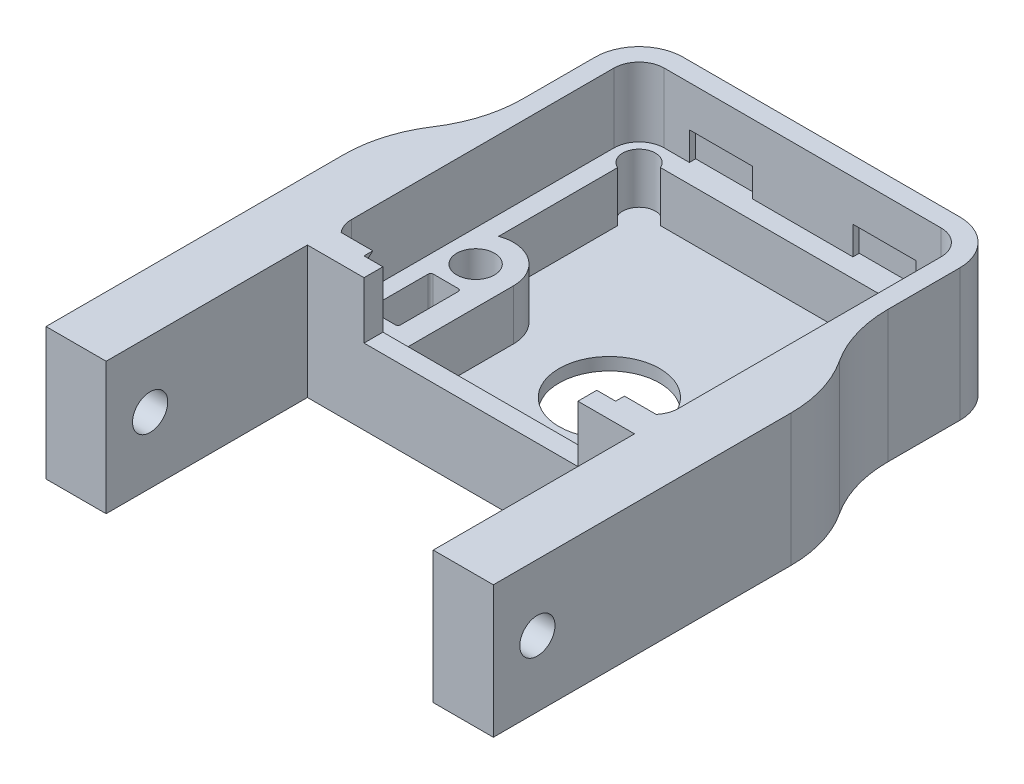
SolidWorks part; units mm, degrees
ref_plane "Front" through (0, 0, 0) normal (0, 0, 1) x (1, 0, 0)
ref_plane "Top" through (0, 0, 0) normal (0, 1, 0) x (1, 0, 0)
ref_plane "Right" through (0, 0, 0) normal (1, 0, 0) x (0, 0, -1)
sketch "Sketch1" plane through (0, 0, 0) normal (0, 1, 0) x (1, 0, 0)
  line L0 (-1.5, 2) -> (-1.5, 22.862)
  line L1 (2, 0) -> (24, 0)
  line L2 (0, 2) -> (0, 22.862)
  line L3 (2, 24.862) -> (24, 24.862)
  line L4 (26, 2) -> (26, 22.862)
  line L5 (2, 26.362) -> (24, 26.362)
  line L6 (27.5, 2) -> (27.5, 22.862)
  line L7 (2, -1.5) -> (24, -1.5)
  line L8 (27.5, 2) -> (27.5, -1.5)
  line L9 (27.5, -1.5) -> (24, -1.5)
  line L10 (-1.5, 2) -> (-1.5, -1.5)
  line L11 (-1.5, -1.5) -> (2, -1.5)
  arc A0 (0, 2) -> (2, 0) centre (2, 2) ccw
  arc A1 (26, 2) -> (24, 0) centre (24, 2) cw
  arc A2 (26, 22.862) -> (24, 24.862) centre (24, 22.862) ccw
  arc A3 (0, 22.862) -> (2, 24.862) centre (2, 22.862) cw
  arc A4 (-1.5, 22.862) -> (2, 26.362) centre (2, 22.862) cw
  arc A5 (27.5, 22.862) -> (24, 26.362) centre (24, 22.862) ccw
  arc A8 (27.5, 2) -> (24, -1.5) centre (24, 2) cw construction
  arc A9 (-1.5, 2) -> (2, -1.5) centre (2, 2) ccw construction
  point P7 (0, 0)
  dimension "D1" = 2
  dimension "D2" = 26
  dimension "D3" = 24.862
  dimension "D4" = 1.5
extrude "Boss-Extrude1" add sketch "Sketch1" along normal blind 9.5
sketch "Sketch3" plane through (0, 0, 0) normal (0, -1, 0) x (1, 0, 0)
  line L0 (24, -26.362) -> (2, -26.362) construction
  line L1 (27.5, 1.5) -> (27.5, -22.862) construction
  line L2 (-1.5, 1.5) -> (27.5, 1.5) construction
  line L3 (-1.5, -22.862) -> (-1.5, 1.5) construction
  line L4 (24, -26.362) -> (2, -26.362)
  line L5 (27.5, 1.5) -> (27.5, -22.862)
  line L6 (-1.5, 1.5) -> (27.5, 1.5)
  line L7 (-1.5, -22.862) -> (-1.5, 1.5)
  arc A0 (-1.5, -22.862) -> (2, -26.362) centre (2, -22.862) ccw construction
  arc A1 (24, -26.362) -> (27.5, -22.862) centre (24, -22.862) ccw construction
  arc A4 (-1.5, -22.862) -> (2, -26.362) centre (2, -22.862) ccw
  arc A5 (24, -26.362) -> (27.5, -22.862) centre (24, -22.862) ccw
extrude "Boss-Extrude2" add sketch "Sketch3" along normal blind 1
sketch "Sketch4" plane through (0, 0, 0) normal (0, 1, 0) x (1, 0, 0)
  line L0 (2, 0) -> (24, 0) construction
  circle A0 centre (13, 9.5) radius 4
  point P8 (13, 0)
  dimension "D1" = 9.5
  dimension "D2" = 8
extrude "Cut-Extrude1" cut sketch "Sketch4" against normal through all both and the other way through all
sketch "Sketch5" plane through (0, 0, 0) normal (0, 1, 0) x (1, 0, 0)
  line L0 (22.8661, 23.362) -> (3.1339, 23.362)
  line L1 (1.5, 21.7281) -> (1.5, 12.1997)
  line L4 (0, 22.862) -> (0, 2)
  line L5 (2, 0) -> (24, 0)
  line L6 (26, 2) -> (26, 22.862)
  line L7 (24, 24.862) -> (2, 24.862)
  line L8 (0, 22.862) -> (0, 2)
  line L9 (2, 0) -> (5.5, 0)
  line L12 (2, 1.5) -> (24, 1.5) construction
  line L13 (5.5, 9.3713) -> (5.5, 0)
  line L14 (13, 63.668) -> (13, -12.944) construction
  line L15 (1.5, 2) -> (3.5, 2)
  line L16 (1.5, 22.862) -> (1.5, 2) construction
  line L17 (24, 23.362) -> (2, 23.362) construction
  line L18 (1.3, 2.2) -> (1.3, 6.8)
  line L19 (1.5, 7) -> (3.5, 7)
  line L20 (3.7, 2.2) -> (3.7, 6.8)
  line L21 (22.3, 2.2) -> (22.3, 6.8)
  line L22 (24, 24.862) -> (2, 24.862) construction
  line L23 (24.5, 2) -> (24.5, 22.862) construction
  line L24 (26, 2) -> (26, 22.862) construction
  line L25 (24.5, 7) -> (22.5, 7)
  line L26 (2, 0) -> (24, 0) construction
  line L27 (24.7, 2.2) -> (24.7, 6.8)
  line L28 (24.5, 2) -> (22.5, 2)
  line L29 (20.5, 9.3713) -> (20.5, 0)
  line L30 (24, 0) -> (20.5, 0)
  line L31 (26, 22.862) -> (26, 2)
  line L32 (24.5, 21.7281) -> (24.5, 12.1997)
  line L33 (2, 24.862) -> (24, 24.862)
  arc A4 (0, 2) -> (2, 0) centre (2, 2) ccw
  arc A5 (24, 0) -> (26, 2) centre (24, 2) ccw
  arc A6 (26, 22.862) -> (24, 24.862) centre (24, 22.862) ccw
  arc A7 (2, 24.862) -> (0, 22.862) centre (2, 22.862) ccw
  arc A8 (0, 2) -> (2, 0) centre (2, 2) ccw
  arc A11 (2, 24.862) -> (0, 22.862) centre (2, 22.862) ccw
  arc A12 (1.5, 2) -> (2, 1.5) centre (2, 2) ccw construction
  arc A13 (24, 1.5) -> (24.5, 2) centre (24, 2) ccw construction
  arc A14 (5.5, 9.3713) -> (1.5, 12.1997) centre (2.5, 9.3713) ccw
  arc A16 (2, 23.362) -> (1.5, 22.862) centre (2, 22.862) ccw construction
  circle A17 centre (2.5, 9.3713) radius 1.5
  arc A18 (3.5, 2) -> (3.7, 2.2) centre (3.5, 2.2) ccw
  circle A19 centre (2.5, 9.3713) radius 3 construction
  arc A20 (1.3, 2.2) -> (1.5, 2) centre (1.5, 2.2) ccw
  arc A21 (3.5, 7) -> (3.7, 6.8) centre (3.5, 6.8) cw
  arc A22 (1.5, 7) -> (1.3, 6.8) centre (1.5, 6.8) ccw
  arc A23 (24.5, 22.862) -> (24, 23.362) centre (24, 22.862) ccw construction
  arc A24 (26, 22.862) -> (24, 24.862) centre (24, 22.862) ccw construction
  arc A25 (24, 0) -> (26, 2) centre (24, 2) ccw construction
  arc A26 (24.5, 7) -> (24.7, 6.8) centre (24.5, 6.8) cw
  arc A27 (22.5, 7) -> (22.3, 6.8) centre (22.5, 6.8) ccw
  arc A28 (24.7, 2.2) -> (24.5, 2) centre (24.5, 2.2) cw
  arc A29 (22.5, 2) -> (22.3, 2.2) centre (22.5, 2.2) cw
  circle A30 centre (23.5, 9.3713) radius 1.5
  arc A31 (22.8661, 23.362) -> (24.5, 21.7281) centre (24, 22.862) cw
  arc A32 (20.5, 9.3713) -> (24.5, 12.1997) centre (23.5, 9.3713) cw
  arc A33 (24, 24.862) -> (26, 22.862) centre (24, 22.862) cw
  arc A34 (26, 2) -> (24, 0) centre (24, 2) cw
  arc A35 (2, 24.862) -> (0, 22.862) centre (2, 22.862) ccw construction
  circle A36 centre (2, 22.862) radius 1.3
  point P7 (13, 23.862)
  point P28 (4.6, 9.362)
  point P48 (2.5, 2)
  point P52 (13, 25.362)
  point P76 (13, 23.362)
  dimension "D3" = 1.5
  dimension "D7" = 2.5
  dimension "D8" = 3
  dimension "D10" = 0.2
  dimension "D11" = 2
  dimension "D12" = 2.5
  dimension "D13" = 5
  dimension "D14" = 2
  dimension "D1" = 0
  dimension "D2" = 1.5
extrude "Boss-Extrude3" add sketch "Sketch5" along normal blind 4
sketch "Sketch6" plane through (0, 0, 1.5) normal (0, 0, 1) x (1, 0, 0)
  line L0 (-1.5, 9.5) -> (27.5, 9.5) construction
  line L1 (4.5, 9.5) -> (21.5, 9.5)
  line L2 (4.5, 9.5) -> (4.5, 5)
  line L3 (4.5, 5) -> (21.5, 5)
  line L4 (21.5, 9.5) -> (21.5, 5)
  line L5 (2, 4) -> (5.5, 4) construction
  point P6 (13, 9.5)
  point P7 (13, 5)
  dimension "D1" = 17
  dimension "D2" = 1
extrude "Cut-Extrude2" cut sketch "Sketch6" against normal blind 3 and the other way through all
sketch "Sketch7" plane through (0, -1, 0) normal (0, -1, 0) x (1, 0, 0)
  line L12 (27.5, -14.1636) -> (30.7793, -9.1276)
  line L13 (27.5, -22.862) -> (27.5, 1.5) construction
  line L14 (30.7793, -9.1276) -> (30.7793, 17.5)
  line L15 (30.7793, 17.5) -> (26, 17.5)
  line L16 (26, 17.5) -> (26, 1.5)
  line L17 (27.5, 1.5) -> (-1.5, 1.5) construction
  line L18 (26, 1.5) -> (27.5, 1.5)
  line L19 (27.5, 1.5) -> (27.5, -14.1636)
  line L20 (26, -2) -> (26, -22.862) construction
  point P4 (21.3935, -8.1637)
  point P6 (27.9888, -4.4195)
  dimension "D1" = 16
extrude "Boss-Extrude4" add sketch "Sketch7" against normal up to surface (10.5 mm away) up to face at (13, 9.5, -10.7414)
ref_plane "Plane1" through (13, 0, 0) normal (1, 0, 0) x (0, 0, -1)
mirror "Mirror1" about plane through (13, 0, 0) normal (1, 0, 0) of "Boss-Extrude4"
sketch "Sketch9" plane through (-4.7793, 0, 0) normal (-1, 0, 0) x (0, 0, 1)
  line L0 (17.5, 9.5) -> (17.5, -1) construction
  circle A0 centre (14, 4.25) radius 1.4
  point P5 (17.5, 4.25)
  dimension "D1" = 3.5
extrude "Cut-Extrude3" cut sketch "Sketch9" against normal through all both and the other way through all
fillet "Fillet1" radius 10 4 edges at (-4.7793, 4.25, -9.1276) (-1.5, 4.25, -14.1636) (30.7793, 4.25, -9.1276) (27.5, 4.25, -14.1636)
sketch "Sketch13" plane through (0, 0, 0) normal (1, 0, 0) x (0, 0, -1)
  line L0 (0, 9.5) -> (0.7, 9.5)
  line L1 (0.7, 9.5) -> (0, 8.9)
  line L2 (0, 8.9) -> (0, 9.5)
  line L3 (22.862, 9.5) -> (2, 9.5) construction
  line L4 (0, 9.5) -> (0, 5) construction
  dimension "D1" = 0.7
  dimension "D2" = 0.6
extrude "Boss-Extrude6" add sketch "Sketch13" along normal blind 3
sketch "Sketch14" plane through (0, 0, -24.862) normal (0, 0, 1) x (1, 0, 0)
  line L0 (4, 4) -> (4, 6.25)
  line L1 (24, 4) -> (2, 4) construction
  line L2 (4, 6.25) -> (9, 6.25)
  line L3 (9, 6.25) -> (9, 4)
  line L4 (9, 4) -> (4, 4)
  line L5 (13, -3.025) -> (13, 3.025) construction
  dimension "D1" = 5
  dimension "D2" = 2.25
  dimension "D3" = 4
extrude "Cut-Extrude4" cut sketch "Sketch14" against normal blind 0.5
mirror "Mirror3" about plane through (13, 0, 0) normal (1, 0, 0) of "Boss-Extrude6", "Cut-Extrude4"
